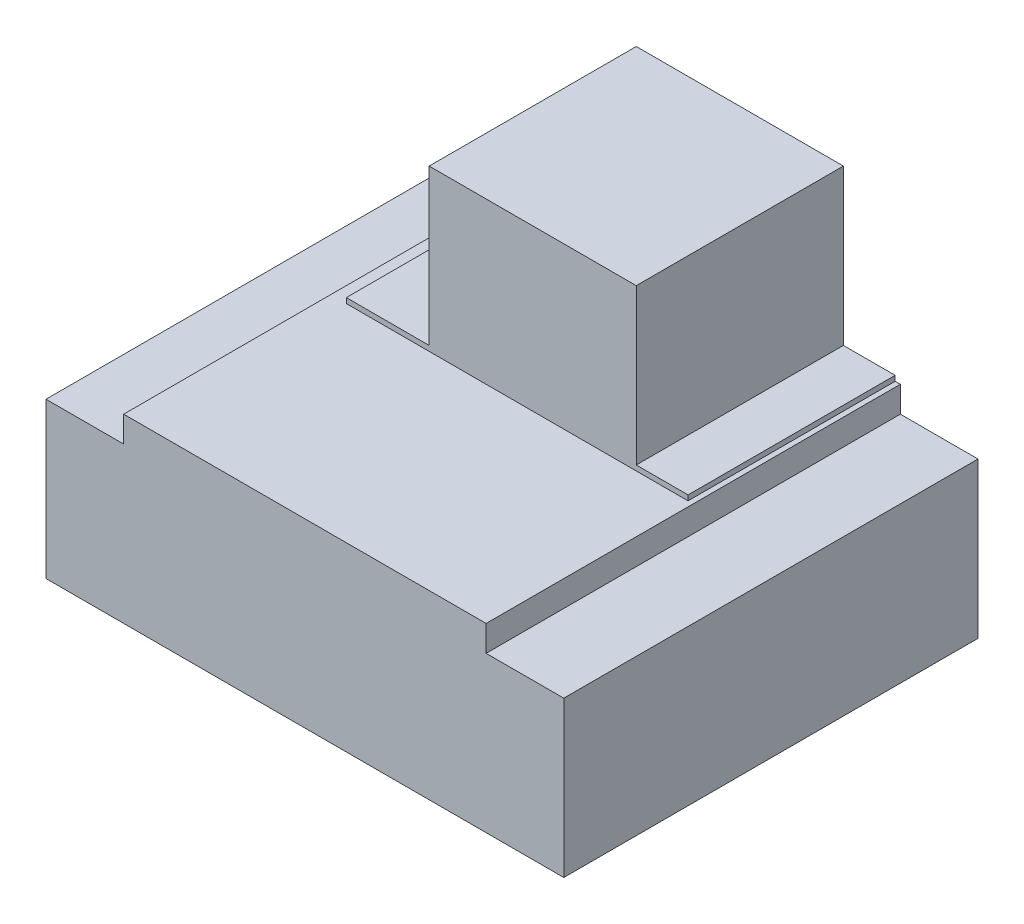
SolidWorks part; units mm, degrees
ref_plane "前视基准面" through (0, 0, 0) normal (0, 0, 1) x (1, 0, 0)
ref_plane "上视基准面" through (0, 0, 0) normal (0, 1, 0) x (1, 0, 0)
ref_plane "右视基准面" through (0, 0, 0) normal (1, 0, 0) x (0, 0, -1)
sketch "草图1" plane through (0, 0, 0) normal (0, 1, 0) x (1, 0, 0)
  line L1 (0, 0) -> (100, 0)
  line L2 (0, 0) -> (0, 80)
  line L3 (0, 80) -> (100, 80)
  line L4 (100, 0) -> (100, 80)
  dimension "D1" = 100
  dimension "D2" = 80
extrude "凸台-拉伸1" add sketch "草图1" along normal blind 35
sketch "草图2" plane through (0, 35, 0) normal (0, 1, 0) x (1, 0, 0)
  line L0 (100, 80) -> (0, 80) construction
  line L1 (18, 80) -> (84, 80)
  line L2 (18, 80) -> (18, 40)
  line L3 (18, 40) -> (84, 40)
  line L4 (84, 80) -> (84, 40)
  line L5 (100, 0) -> (100, 80) construction
  line L6 (0, 80) -> (0, 0) construction
  dimension "D1" = 16
  dimension "D2" = 18
  dimension "D3" = 40
extrude "凸台-拉伸2" add sketch "草图2" along normal blind 1
sketch "草图3" plane through (0, 36, 0) normal (0, 1, 0) x (1, 0, 0)
  line L0 (84, 80) -> (18, 80) construction
  line L1 (34, 80) -> (74, 80)
  line L2 (34, 80) -> (34, 40)
  line L3 (34, 40) -> (74, 40)
  line L4 (74, 80) -> (74, 40)
  line L5 (84, 40) -> (84, 80) construction
  dimension "D1" = 40
  dimension "D2" = 40
  dimension "D3" = 10
extrude "凸台-拉伸3" add sketch "草图3" along normal blind 30
sketch "草图4" plane through (0, 35, 0) normal (0, 1, 0) x (1, 0, 0)
  line L0 (0, 0) -> (100, 0) construction
  line L1 (0, 80) -> (15, 80)
  line L2 (0, 80) -> (0, 0)
  line L3 (0, 0) -> (15, 0)
  line L4 (15, 80) -> (15, 0)
  line L6 (100, 80) -> (85, 80)
  line L7 (100, 80) -> (100, 0)
  line L8 (100, 0) -> (85, 0)
  line L9 (85, 80) -> (85, 0)
  dimension "D1" = 15
  dimension "D2" = 15
extrude "切除-拉伸1" cut sketch "草图4" against normal blind 5
